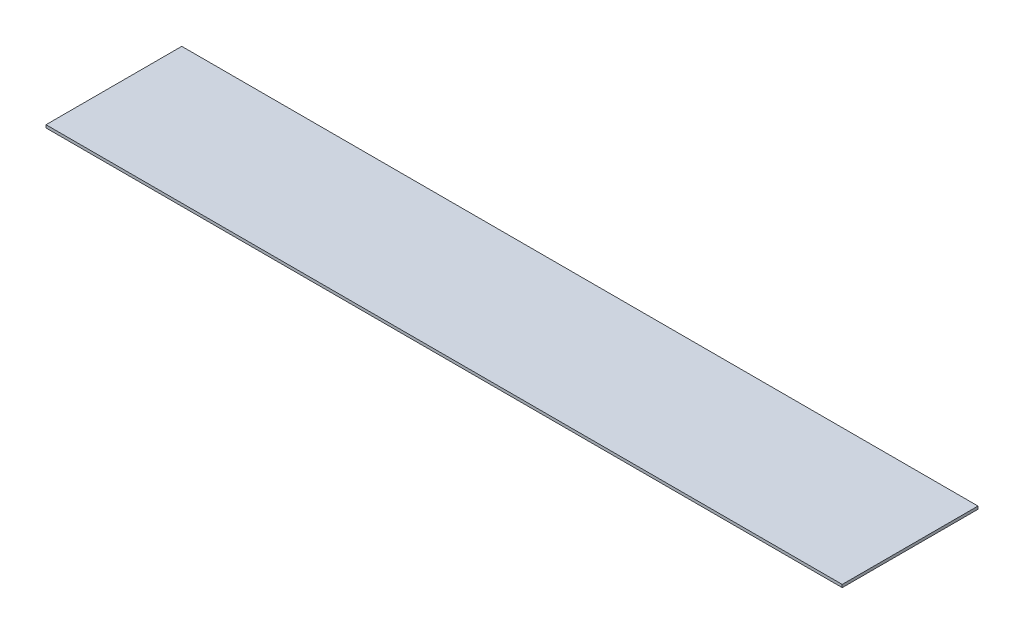
SolidWorks part; units mm, degrees
ref_plane "Front Plane" through (0, 0, 0) normal (0, 0, 1) x (1, 0, 0)
ref_plane "Top Plane" through (0, 0, 0) normal (0, 1, 0) x (1, 0, 0)
ref_plane "Right Plane" through (0, 0, 0) normal (1, 0, 0) x (0, 0, -1)
sketch "Sketch1" plane through (0, 0, 0) normal (0, 1, 0) x (1, 0, 0)
  line L1 (-893.7625, -152.4) -> (893.7625, -152.4)
  line L2 (-893.7625, -152.4) -> (-893.7625, 152.4)
  line L3 (-893.7625, 152.4) -> (893.7625, 152.4)
  line L4 (893.7625, -152.4) -> (893.7625, 152.4)
  line L5 (-893.7625, -152.4) -> (893.7625, 152.4) construction
  line L6 (-893.7625, 152.4) -> (893.7625, -152.4) construction
  point P0 (0, 0)
  dimension "D1" = 1787.525
  dimension "D2" = 304.8
extrude "Boss-Extrude1" add sketch "Sketch1" along normal blind 6.35
